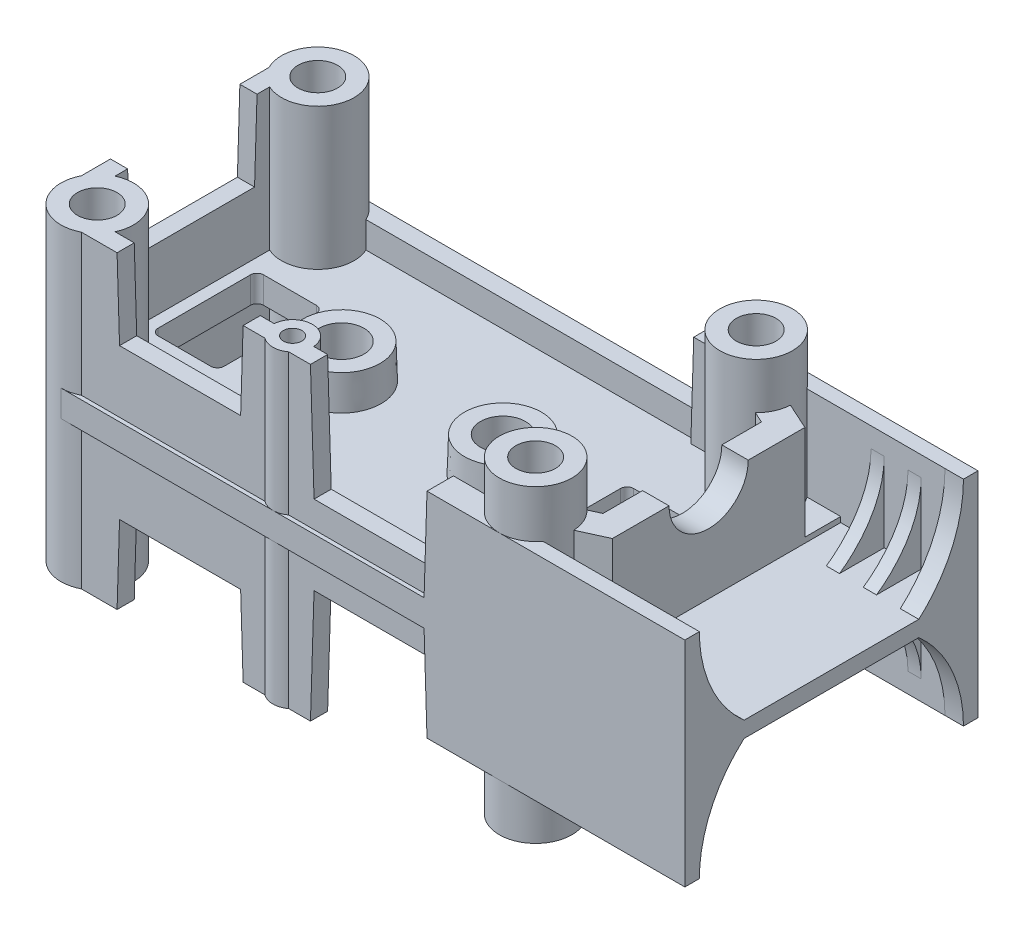
SolidWorks part; units mm, degrees
ref_plane "Front Plane" through (0, 0, 0) normal (0, 0, 1) x (1, 0, 0)
ref_plane "Top Plane" through (0, 0, 0) normal (0, 1, 0) x (1, 0, 0)
ref_plane "Right Plane" through (0, 0, 0) normal (1, 0, 0) x (0, 0, -1)
sketch "Sketch1" plane through (0, 0, 0) normal (0, 1, 0) x (1, 0, 0)
  line L1 (16.6, -8.35) -> (-16.6, -8.35) construction
  line L2 (16.6, -8.35) -> (16.6, 8.35) construction
  line L3 (16.6, 8.35) -> (-16.6, 8.35) construction
  line L4 (-16.6, -8.35) -> (-16.6, 8.35) construction
  line L5 (16.6, -8.35) -> (-16.6, 8.35) construction
  line L6 (16.6, 8.35) -> (-16.6, -8.35) construction
  circle A0 centre (-16.6, 8.35) radius 2.75
  circle A1 centre (-16.6, -8.35) radius 2.75
  circle A2 centre (16.6, -8.35) radius 2.75
  circle A3 centre (16.6, 8.35) radius 2.75
  point P0 (0, 0)
  dimension "D1" = 5.5
  dimension "D2" = 16.7
  dimension "D3" = 33.2
extrude "Boss-Extrude1" add sketch "Sketch1" along normal blind 10.7
sketch "Sketch2" plane through (0, 10.7, 0) normal (0, 1, 0) x (1, 0, 0)
  line L1 (-19.35, 11.1) -> (30.65, 11.1)
  line L2 (-19.35, 11.1) -> (-19.35, -11.1)
  line L3 (-19.35, -11.1) -> (30.65, -11.1)
  line L4 (30.65, 11.1) -> (30.65, -11.1)
  circle A3 centre (-16.6, 8.35) radius 2.75 construction
  circle A4 centre (-16.6, -8.35) radius 2.75 construction
  arc A5 (-16.6, -11.1) -> (-19.35, -8.35) centre (-16.6, -8.35) cw
  arc A6 (-16.6, 11.1) -> (-19.35, 8.35) centre (-16.6, 8.35) ccw
  circle M5 centre (-16.6, -8.35) radius 2.75
  dimension "D1" = 50
extrude "Boss-Extrude2" add sketch "Sketch2" along normal blind 1 contours L1 A6 L2 L3 L4 M5 | M5
sketch "Sketch3" plane through (-19.35, 0, 0) normal (-1, 0, 0) x (0, 0, 1)
  line L1 (-8.35, 10.7) -> (8.35, 10.7)
  line L2 (-8.35, 10.7) -> (-8.35, 0)
  line L3 (-8.35, 0) -> (8.35, 0)
  line L4 (8.35, 10.7) -> (8.35, 0)
  line L6 (-4.9, 0) -> (4.9, 0)
  line L7 (-4.9, 0) -> (-4.7125, 6)
  line L8 (-4.7125, 6) -> (4.7125, 6)
  line L9 (4.9, 0) -> (4.7125, 6)
  point P10 (0, 0)
  point P11 (0, 0)
  point P13 (0, 6)
  line M9 (-8.35, 10.7) -> (8.35, 10.7)
  dimension "D1" = 9.8
  dimension "D2" = 88.21
  dimension "D3" = 6
extrude "Boss-Extrude3" add sketch "Sketch3" against normal blind 1.3 from offset 0.3 contours L9 L3 L4 L2 L7 L8 M9 offset against normal yes
sketch "Sketch5" plane through (0, 10.7, 0) normal (0, -1, 0) x (1, 0, 0)
  line L0 (30.65, 9.1) -> (30.65, 10)
  line L1 (30.65, 11.1) -> (10.9, 11.1)
  line L2 (30.65, 11.1) -> (30.65, 9.1)
  line L3 (30.65, 9.1) -> (10.9, 9.1)
  line L4 (10.9, 11.1) -> (10.9, 9.1)
  line L5 (30.65, -11.1) -> (10.9, -11.1)
  line L6 (30.65, -11.1) -> (30.65, -9.1)
  line L7 (30.65, -9.1) -> (10.9, -9.1)
  line L8 (10.9, -11.1) -> (10.9, -9.1)
  line L9 (30.65, 9.1) -> (16.6, 9.1)
  line L10 (30.65, 10) -> (16.6, 10)
  line L11 (16.6, 9.1) -> (16.6, 10)
  line L12 (30.65, -9.1) -> (30.65, -10)
  line L13 (30.65, -9.1) -> (16.6, -9.1)
  line L14 (30.65, -10) -> (16.6, -10)
  line L15 (16.6, -9.1) -> (16.6, -10)
  line M11 (-16.6, -11.1) -> (16.6, -11.1)
  circle M12 centre (16.6, -8.35) radius 2.75
  line M13 (16.6, -11.1) -> (30.65, -11.1)
  line M14 (30.65, -11.1) -> (30.65, 11.1)
  line M15 (30.65, 11.1) -> (16.6, 11.1)
  circle M16 centre (16.6, 8.35) radius 2.75
  line M17 (16.6, 11.1) -> (-16.6, 11.1)
  dimension "D1" = 2
  dimension "D2" = 5.7
  dimension "D3" = 0.9
extrude "Boss-Extrude4" add sketch "Sketch5" along normal blind 7.1 contours L10 M14 M15 M16 | L4 L3 M17 M16 | L14 M14 M12 M13 | L8 L7 M11 M12
sketch "Sketch6" plane through (0, 0, 11.1) normal (0, 0, 1) x (1, 0, 0)
  line L0 (10.9, 10.7) -> (11.1219, 3.6)
  line L1 (10.9, 3.6) -> (10.9, 10.7) construction
  line L2 (11.1219, 3.6) -> (10.9, 3.6)
  line L3 (10.9, 3.6) -> (10.9, 10.7)
  dimension "D1" = 88.21
extrude "Cut-Extrude1" cut sketch "Sketch6" against normal up to surface (22.2 mm away)
sketch "Sketch8" plane through (0, 0, -11.1) normal (0, 0, -1) x (-1, 0, 0)
  line L0 (16.6, 10.7) -> (-10.9625, 10.7)
  line L1 (16.6, 10.7) -> (16.6, 8.7)
  line L2 (-10.9625, 10.7) -> (-10.9625, 8.7)
  line L3 (16.6, 8.7) -> (-10.9625, 8.7)
  line L4 (-11.1219, 3.6) -> (-10.9, 10.7) construction
  dimension "D1" = 2
extrude "Boss-Extrude5" add sketch "Sketch8" against normal blind 1.3 from offset 0.3 offset against normal yes
sketch "Sketch9" plane through (0, 0, 11.1) normal (0, 0, 1) x (1, 0, 0)
  line L0 (-16.6, 10.7) -> (-16.6, 0)
  line L1 (-16.6, 0) -> (-12.65, 0)
  line L2 (-12.65, 0) -> (-12.4625, 6)
  line L3 (-12.4625, 6) -> (-3.2919, 6)
  line L4 (-3.2919, 6) -> (-3.1044, 0)
  line L5 (-3.1044, 0) -> (1.9956, 0)
  line L6 (1.9956, 0) -> (2.2675, 8.7)
  line L7 (2.2675, 8.7) -> (10.9625, 8.7)
  line L8 (11.1219, 3.6) -> (10.9, 10.7) construction
  line L9 (10.9625, 8.7) -> (10.9, 10.7)
  line L10 (10.9, 10.7) -> (-16.6, 10.7)
  line L11 (-17.75, 6) -> (-19.05, 6) construction
  line L12 (-12.65, 0) -> (-3.1044, 0) construction
  point P17 (-7.8772, 0)
  point P18 (-7.8772, 6)
  dimension "D1" = 88.21
  dimension "D2" = 5.1
  dimension "D3" = 6.7
  dimension "D4" = 2
  dimension "D5" = 9.5456
extrude "Boss-Extrude6" add sketch "Sketch9" against normal blind 1.3 from offset 0.3 offset against normal yes
sketch "Sketch10" plane through (0, 0, 0) normal (0, -1, 0) x (1, 0, 0)
  line L0 (-16.6, 11.1) -> (10.9, 11.1) construction
  line L1 (-3.1044, 10.8) -> (1.9956, 10.8) construction
  circle A0 centre (-0.5544, 9.6) radius 1.5
  point P6 (-0.5544, 10.8)
  dimension "D1" = 3
extrude "Boss-Extrude7" add sketch "Sketch10" against normal up to surface (10.7 mm away) up to face at (7.9068, 10.7, 0)
sketch "Sketch11" plane through (0, 0, 0) normal (0, -1, 0) x (1, 0, 0)
  circle A1 centre (-16.6, 8.35) radius 1.5
  circle A2 centre (16.6, 8.35) radius 1.5
  circle A3 centre (16.6, -8.35) radius 1.5
  circle A5 centre (-16.6, -8.35) radius 1.5
  dimension "D1" = 3
extrude "Cut-Extrude2" cut sketch "Sketch11" against normal up to surface (10.7 mm away) up to face at (6.8492, 10.7, 1.1)
sketch "Sketch12" plane through (0, 0, 0) normal (0, -1, 0) x (1, 0, 0)
  circle A0 centre (-0.5544, 9.6) radius 0.7
  dimension "D1" = 1.4
extrude "Cut-Extrude3" cut sketch "Sketch12" against normal blind 2.5
sketch "Sketch13" plane through (0, 10.7, 0) normal (0, -1, 0) x (1, 0, 0)
  circle A0 centre (-6.45, 0) radius 3
  circle A1 centre (5.7736, 0) radius 3
  circle A2 centre (-16.6, 8.35) radius 1.5 construction
  circle A3 centre (-6.45, 0) radius 1.7 construction
  circle A4 centre (5.7736, 0) radius 1.7 construction
  point P5 (0, 0)
  point P6 (-4.75, 0)
  point P8 (4.0736, 0)
  dimension "D1" = 6
  dimension "D2" = 10.15
  dimension "D4" = 3.4
  dimension "D3" = 8.8236
extrude "Boss-Extrude8" add sketch "Sketch13" along normal blind 2.6 draft 1.79
sketch "Sketch14" plane through (0, 8.1, 0) normal (0, -1, 0) x (1, 0, 0)
  circle A0 centre (-6.45, 0) radius 1.7
  circle A1 centre (5.7736, 0) radius 1.7
  dimension "D1" = 3.4
extrude "Cut-Extrude4" cut sketch "Sketch14" against normal up to surface (3.6 mm away) up to face at (-1.9565, 11.7, 0)
sketch "Sketch15" plane through (0, 10.7, 0) normal (0, -1, 0) x (1, 0, 0)
  line L1 (-16.85, 4) -> (-11.85, 4)
  line L2 (-16.85, 4) -> (-16.85, -4)
  line L3 (-16.85, -4) -> (-11.85, -4)
  line L4 (-11.85, 4) -> (-11.85, -4)
  line L5 (11.1736, 4) -> (18.1736, 4)
  line L6 (11.1736, 4) -> (11.1736, -4)
  line L7 (11.1736, -4) -> (18.1736, -4)
  line L8 (18.1736, 4) -> (18.1736, -4)
  line L9 (-6.45, 0) -> (-11.85, 0) construction
  line L12 (5.7736, 0) -> (11.1736, 0) construction
  circle A3 centre (-6.45, 0) radius 1.7 construction
  point P8 (0, 0)
  point P9 (-16.85, 0)
  point P11 (11.1736, 0)
  point P13 (-8.15, 0)
  dimension "D1" = 8
  dimension "D2" = 7
  dimension "D3" = 5
  dimension "D4" = 3.7
extrude "Cut-Extrude5" cut sketch "Sketch15" against normal up to surface (1 mm away) up to face at (-6.45, 11.7, 1.7)
sketch "Sketch16" plane through (0, 10.7, 0) normal (0, -1, 0) x (1, 0, 0)
  line L0 (19.3459, 8.2) -> (18.5181, 6.3794)
  line L1 (19.3459, 8.2) -> (21.35, 7.2888)
  line L2 (18.5181, 6.3794) -> (20.5222, 5.4681)
  line L3 (21.35, 7.2888) -> (20.5222, 5.4681)
  line L4 (19.3459, -8.2) -> (18.5181, -6.3794)
  line L5 (19.3459, -8.2) -> (21.35, -7.2888)
  line L6 (18.5181, -6.3794) -> (20.5222, -5.4681)
  line L7 (21.35, -7.2888) -> (20.5222, -5.4681)
  line L8 (21.35, 7.2888) -> (21.35, -7.2888)
  line L9 (21.35, 7.2888) -> (19.35, 7.2888)
  line L10 (21.35, -7.2888) -> (19.35, -7.2888)
  line L11 (19.35, 7.2888) -> (19.35, -7.2888)
  circle A0 centre (16.6, 8.35) radius 2.75 construction
  circle A1 centre (16.6, -8.35) radius 2.75 construction
  arc M32 (13.9542, -9.1) -> (18.8, -10) centre (16.6, -8.35) cw
  arc M36 (18.8, 10) -> (13.9542, 9.1) centre (16.6, 8.35) cw
  dimension "D1" = 2.8319
  dimension "D2" = 16.4
  dimension "D3" = 2
extrude "Boss-Extrude9" add sketch "Sketch16" along normal blind 7.2 contours L11 L9 L1 L2 M36 | L9 L11 L2 L3 | L2 L11 L6 L7 L8 L3 | L6 L11 L10 L7 | L11 L6 L5 L10 M32
sketch "Sketch17" plane through (21.35, 0, 0) normal (1, 0, 0) x (0, 0, -1)
  line L0 (-7.2888, 3.5) -> (7.2888, 3.5) construction
  circle A0 centre (0, 3.5) radius 3
  dimension "D1" = 6
extrude "Cut-Extrude6" cut sketch "Sketch17" against normal up to surface (2 mm away) up to face at (19.35, 7.1, 0)
sketch "Sketch18" plane through (0, 10.7, 0) normal (0, -1, 0) x (1, 0, 0)
  line L0 (30.65, 10) -> (30.65, -10)
  line L1 (30.65, 10) -> (21.35, 10)
  line L2 (30.65, -10) -> (21.35, -10)
  line L3 (21.35, 10) -> (21.35, -10)
  line L4 (21.35, 7.2888) -> (21.35, -7.2888) construction
extrude "Cut-Extrude7" cut sketch "Sketch18" against normal blind 0.4
fillet "Fillet1" radius 0.5 8 edges at (11.1736, 11.2, -4) (18.1736, 11.2, -4) (18.1736, 11.2, 4) (11.1736, 11.2, 4) (-11.85, 11.2, -4) (-11.85, 11.2, 4) (-16.85, 11.2, -4) (-16.85, 11.2, 4)
sketch "Sketch19" plane through (30.65, 0, 0) normal (1, 0, 0) x (0, 0, -1)
  line L0 (10, 3.6) -> (10, 11.1)
  line L1 (10, 11.1) -> (6.6144, 11.1)
  line L2 (10, 11.1) -> (-10, 11.1) construction
  line L3 (-10, 11.1) -> (-10, 3.6)
  line L4 (-10, 11.1) -> (-6.6144, 11.1)
  line L5 (-10, 3.6) -> (-10, 11.1) construction
  line L6 (11.1, 11.7) -> (-11.1, 11.7) construction
  line L7 (11.1, 3.6) -> (10, 3.6) construction
  ellipse E0 centre (0, 3.6) end of major axis (10, 3.6) minor radius 10
  point P37 (0, 11.7)
  line M2 (-10, 3.6) -> (-10, 11.1)
  line M3 (-10, 11.1) -> (10, 11.1)
  line M4 (10, 11.1) -> (10, 3.6)
  dimension "D1" = 20
extrude "Boss-Extrude10" add sketch "Sketch19" against normal blind 1.4 contours E0 M4 M3 | E0 M3 M2
sketch "Sketch20" plane through (30.65, 0, 0) normal (1, 0, 0) x (0, 0, -1)
  line L0 (-10, 5.1) -> (-10, 11.1)
  line L1 (-10, 11.1) -> (-6.6144, 11.1)
  line L2 (6.6144, 11.1) -> (10, 11.1)
  line L3 (10, 11.1) -> (10, 5.1)
  line L8 (-10, 3.6) -> (-10, 11.1) construction
  line L9 (10, 11.1) -> (10, 3.6) construction
  ellipse E0 centre (0, 5.1) end of major axis (10, 5.1) minor radius 8
  ellipse M2 centre (0, 3.6) end of major axis (10, 3.6) minor radius 10 (-10, 3.6) -> (-6.6144, 11.1) cw
  ellipse M4 centre (0, 3.6) end of major axis (10, 3.6) minor radius 10 (6.6144, 11.1) -> (10, 3.6) cw
  dimension "D1" = 1.5
extrude "Boss-Extrude11" add sketch "Sketch20" against normal blind 1 from offset 3.2 contours L1 L0 M2 | L3 L2 M4 offset against normal yes
sketch "Sketch21" plane through (30.65, 0, 0) normal (1, 0, 0) x (0, 0, -1)
  line L0 (-6.6144, 11.1) -> (-10, 11.1)
  line L1 (-10, 11.1) -> (-10, 5.1)
  line L2 (6.6144, 11.1) -> (10, 11.1)
  line L3 (10, 11.1) -> (10, 5.1)
  line L4 (10, 11.1) -> (10, 5.1) construction
  line L5 (-10, 5.1) -> (-10, 11.1) construction
  ellipse E0 centre (0, 5.1) end of major axis (-10, 5.1) minor radius 8
  ellipse M2 centre (0, 3.6) end of major axis (10, 3.6) minor radius 10 (-10, 3.6) -> (-6.6144, 11.1) cw
  ellipse M4 centre (0, 3.6) end of major axis (10, 3.6) minor radius 10 (6.6144, 11.1) -> (10, 3.6) cw
  dimension "D1" = 1.5
extrude "Boss-Extrude12" add sketch "Sketch21" against normal blind 1 from offset 6 contours L3 L2 M4 | L0 L1 M2 offset against normal yes
mirror "Mirror2" about plane through (0, 11.7, 0) normal (0, 1, 0) of bodies 122
